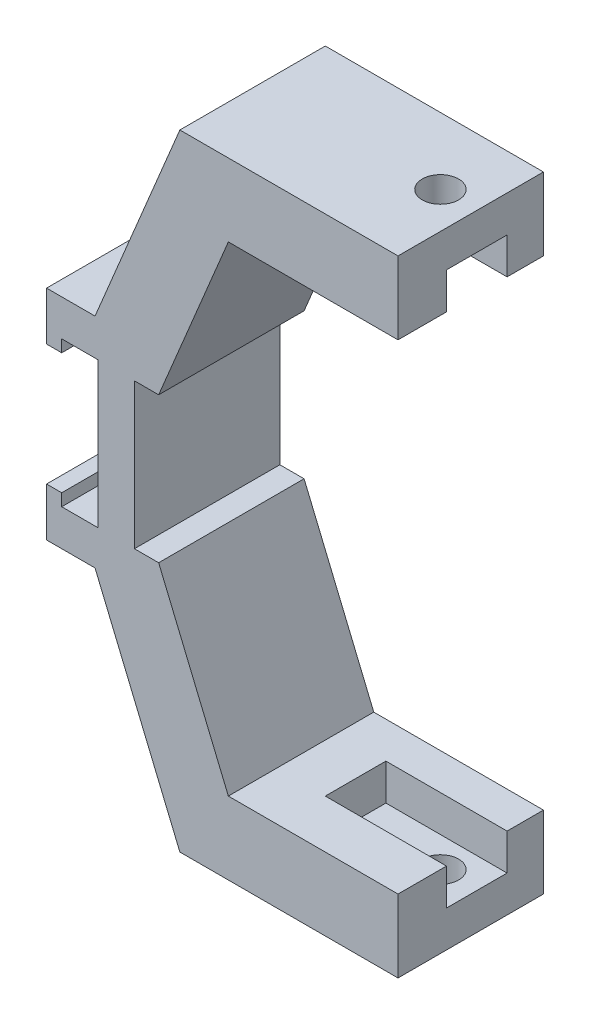
SolidWorks part; units mm, degrees
ref_plane "Front Plane" through (0, 0, 0) normal (0, 0, 1) x (1, 0, 0)
ref_plane "Top Plane" through (0, 0, 0) normal (0, 1, 0) x (1, 0, 0)
ref_plane "Right Plane" through (0, 0, 0) normal (1, 0, 0) x (0, 0, -1)
sketch "Sketch1" plane through (0, 0, 0) normal (0, 0, 1) x (1, 0, 0)
  line L0 (-9.0359, 9.3303) -> (-16.0359, -7.4697)
  line L1 (8.9641, 9.3303) -> (-9.0359, 9.3303)
  line L2 (8.9641, 9.3303) -> (8.9641, 3.3303)
  line L3 (8.9641, 3.3303) -> (-5.0359, 3.3303)
  line L5 (-16.0359, -7.4697) -> (-20.0359, -7.4697)
  line L6 (-20.0359, -7.4697) -> (-20.0359, -11.4697)
  line L7 (-20.0359, -11.4697) -> (-18.7859, -11.4697)
  line L8 (-18.7859, -11.4697) -> (-18.7859, -10.4697)
  line L9 (-18.7859, -10.4697) -> (-15.7859, -10.4697)
  line L10 (-10.7859, -10.4697) -> (-5.0359, 3.3303)
  line L11 (-12.7859, -10.4697) -> (-10.7859, -10.4697)
  line L13 (-15.7859, -10.4697) -> (-15.7859, -16.4697)
  line L14 (-15.7859, -16.4697) -> (-12.7859, -16.4697)
  line L15 (-12.7859, -10.4697) -> (-12.7859, -16.4697)
  dimension "D1" = 18
  dimension "D2" = 6
  dimension "D3" = 29
  dimension "D4" = 6
  dimension "D5" = 14
  dimension "D6" = 4
  dimension "D7" = 8
  dimension "D8" = 1
  dimension "D9" = 2
  dimension "D10" = 3
  dimension "D11" = 6
  dimension "D12" = 4
extrude "Boss-Extrude1" add sketch "Sketch1" along normal blind 12
sketch "Sketch2" plane through (8.9641, 0, 0) normal (1, 0, 0) x (0, 0, -1)
  line L0 (-12, 3.3303) -> (0, 3.3303) construction
  line L1 (-8, 6.3303) -> (-3, 6.3303)
  line L2 (-8, 6.3303) -> (-8, 3.3303)
  line L3 (-8, 3.3303) -> (-3, 3.3303)
  line L4 (-3, 6.3303) -> (-3, 3.3303)
  line L6 (0, 3.3303) -> (0, 9.3303) construction
  dimension "D1" = 5
  dimension "D2" = 3
  dimension "D3" = 3
extrude "Cut-Extrude1" cut sketch "Sketch2" against normal blind 10
sketch "Sketch3" plane through (0, 9.3303, 0) normal (0, 1, 0) x (1, 0, 0)
  line L0 (8.9641, 0) -> (-9.0359, 0) construction
  line L1 (8.9641, -12) -> (8.9641, 0) construction
  circle A0 centre (5.9641, -5.5) radius 1.5
  dimension "D3" = 3
  dimension "D1" = 5.5
  dimension "D2" = 3
extrude "Cut-Extrude2" cut sketch "Sketch3" against normal up to next
mirror "Mirror1" about plane through (-15.7859, -16.4697, 12) normal (0, 1, 0) of "Cut-Extrude2", "Cut-Extrude1", "Boss-Extrude1"
